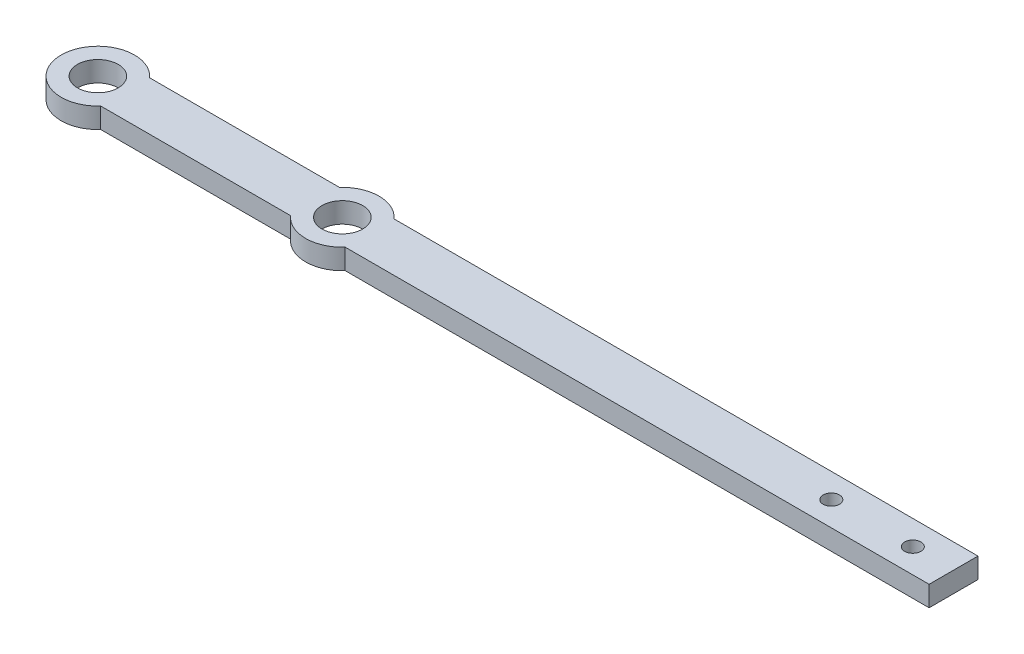
SolidWorks part; units mm, degrees
ref_plane "Front Plane" through (0, 0, 0) normal (0, 0, 1) x (1, 0, 0)
ref_plane "Top Plane" through (0, 0, 0) normal (0, 1, 0) x (1, 0, 0)
ref_plane "Right Plane" through (0, 0, 0) normal (1, 0, 0) x (0, 0, -1)
sketch "Sketch1" plane through (0, 0, 0) normal (0, 1, 0) x (1, 0, 0)
  line L0 (6.7082, 6) -> (53.2918, 6)
  line L1 (6.7082, -6) -> (53.2918, -6)
  line L2 (66.7082, 6) -> (210, 6)
  line L3 (210, 6) -> (210, -6)
  line L4 (210, -6) -> (66.7082, -6)
  arc A0 (6.7082, 6) -> (6.7082, -6) centre (0, 0) ccw
  arc A1 (53.2918, -6) -> (66.7082, -6) centre (60, 0) ccw
  arc A2 (66.7082, 6) -> (53.2918, 6) centre (60, 0) ccw
  dimension "D1" = 18
  dimension "D2" = 18
  dimension "D3" = 6
  dimension "D4" = 60
  dimension "D5" = 150
extrude "Boss-Extrude1" add sketch "Sketch1" along normal blind 5
sketch "Sketch2" plane through (0, 5, 0) normal (0, 1, 0) x (1, 0, 0)
  line L0 (210, -6) -> (210, 6) construction
  circle A0 centre (0, 0) radius 5
  circle A1 centre (60, 0) radius 5
  circle A2 centre (200, 0) radius 2
  circle A3 centre (180, 0) radius 2
  dimension "D1" = 10
  dimension "D2" = 10
  dimension "D3" = 4
  dimension "D4" = 10
  dimension "D5" = 20
extrude "Cut-Extrude1" cut sketch "Sketch2" against normal through all
